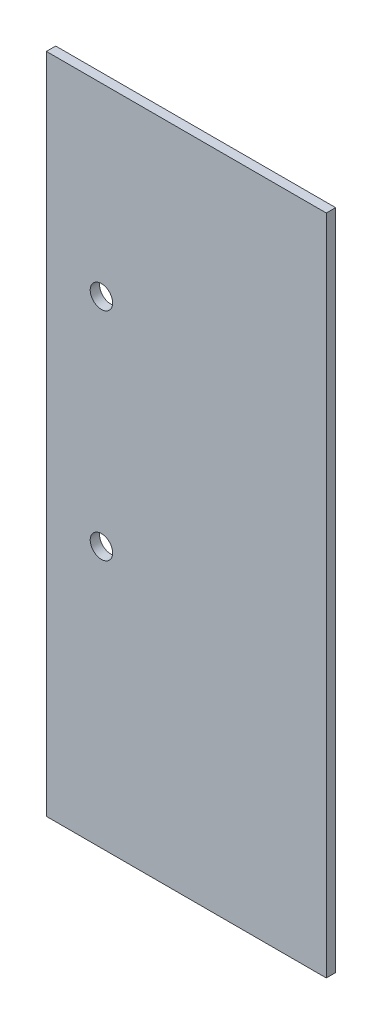
SolidWorks part; units mm, degrees
ref_plane "Plan de face" through (0, 0, 0) normal (0, 0, 1) x (1, 0, 0)
ref_plane "Plan de dessus" through (0, 0, 0) normal (0, 1, 0) x (1, 0, 0)
ref_plane "Plan de droite" through (0, 0, 0) normal (1, 0, 0) x (0, 0, -1)
sketch "Esquisse1" plane through (0, 0, 0) normal (0, 0, 1) x (1, 0, 0)
  line L1 (-75, 177.5) -> (75, 177.5)
  line L2 (-75, 177.5) -> (-75, -177.5)
  line L3 (-75, -177.5) -> (75, -177.5)
  line L4 (75, 177.5) -> (75, -177.5)
  line L5 (-75, 177.5) -> (75, -177.5) construction
  line L6 (-75, -177.5) -> (75, 177.5) construction
  point P0 (0, 0)
  dimension "D1" = 355
  dimension "D2" = 150
extrude "Boss.-Extru.1" add sketch "Esquisse1" along normal blind 5
sketch "Esquisse2" plane through (0, 0, 5) normal (0, 0, 1) x (1, 0, 0)
  line L1 (75, 177.5) -> (-75, 177.5) construction
  line L2 (-75, 177.5) -> (-75, -177.5) construction
  line L3 (-45.5, 78.5) -> (-45.5, -37.5) construction
  circle A1 centre (-45.5, 78.5) radius 6
  circle A2 centre (-45.5, -37.5) radius 6
  dimension "D1" = 12
  dimension "D5" = 12
  dimension "D2" = 99
  dimension "D3" = 29.5
  dimension "D4" = 116
extrude "Enlèv. mat.-Extru.1" cut sketch "Esquisse2" against normal blind 20
sketch "Esquisse3" plane through (0, 0, 0) normal (0, 0, -1) x (-1, 0, 0)
  circle A0 centre (1.1887, 154.4726) radius 1.5
  circle A1 centre (51.9063, 163.4455) radius 1.5
  circle A2 centre (7.5292, 118.5548) radius 1.5
  circle A3 centre (58.2463, 127.5003) radius 1.5
  circle A4 centre (7.5292, -77.5848) radius 1.5
  circle A5 centre (58.2463, -86.5303) radius 1.5
  circle A6 centre (1.1887, -113.5026) radius 1.5
  circle A7 centre (51.9063, -122.4755) radius 1.5
extrude "Enlèv. mat.-Extru.2" cut sketch "Esquisse3" against normal blind 2.25
